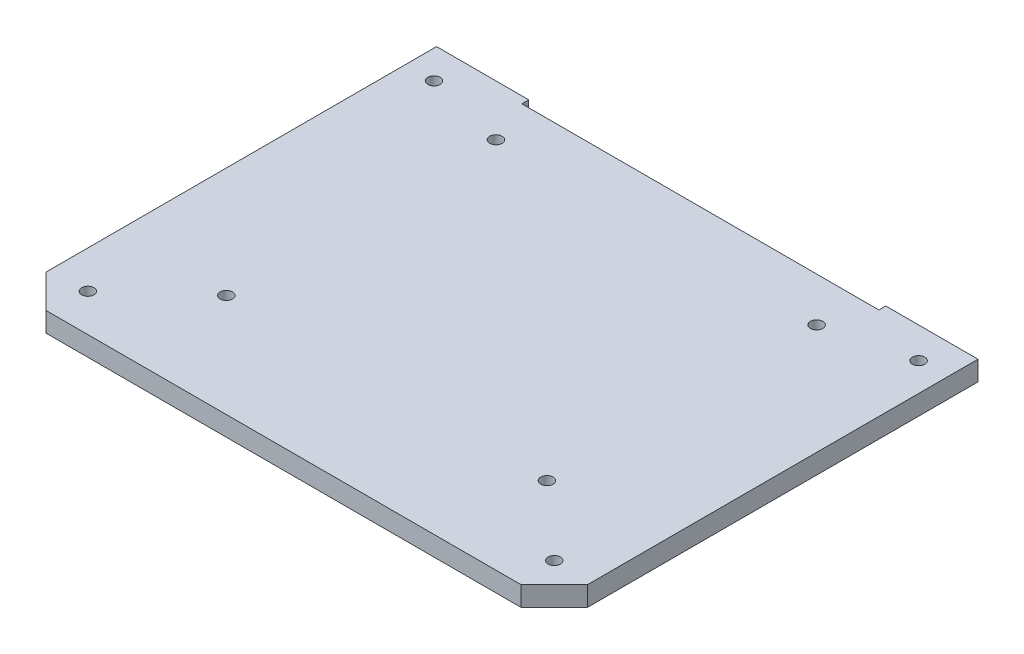
SolidWorks part; units mm, degrees
ref_plane "Front Plane" through (0, 0, 0) normal (0, 0, 1) x (1, 0, 0)
ref_plane "Top Plane" through (0, 0, 0) normal (0, 1, 0) x (1, 0, 0)
ref_plane "Right Plane" through (0, 0, 0) normal (1, 0, 0) x (0, 0, -1)
ref_plane "PZ28" through (0, 28, 0) normal (0, 1, 0) x (1, 0, 0)
sketch "Sketch1" plane through (0, 28, 0) normal (0, 1, 0) x (1, 0, 0)
  line L0 (-65.187, -126.3) -> (65.187, -126.3)
  line L1 (65.187, -126.3) -> (74.3, -117.187)
  line L2 (74.3, -117.187) -> (74.3, -11.9)
  line L3 (74.3, -11.9) -> (-74.3, -11.9)
  line L4 (-74.3, -11.9) -> (-74.3, -117.187)
  line L5 (-74.3, -117.187) -> (-65.187, -126.3)
extrude "Lid Plate" add sketch "Sketch1" along normal blind 2.4
ref_plane "PZ25" through (0, 25, 0) normal (0, 1, 0) x (1, 0, 0)
sketch "Sketch2" plane through (0, 25, 0) normal (0, 1, 0) x (1, 0, 0)
  line L0 (74.3, -11.9) -> (74.3, -117.187)
  line L1 (74.3, -117.187) -> (65.187, -126.3)
  line L2 (65.187, -126.3) -> (-65.187, -126.3)
  line L3 (-65.187, -126.3) -> (-74.3, -117.187)
  line L4 (-74.3, -117.187) -> (-74.3, -11.9)
  line L5 (-74.3, -11.9) -> (-72.7, -11.9)
  line L6 (-72.7, -11.9) -> (-72.7, -116.5243)
  line L7 (-72.7, -116.5243) -> (-64.5243, -124.7)
  line L8 (-64.5243, -124.7) -> (64.5243, -124.7)
  line L9 (64.5243, -124.7) -> (72.7, -116.5243)
  line L10 (72.7, -116.5243) -> (72.7, -11.9)
  line L11 (72.7, -11.9) -> (74.3, -11.9)
extrude "Drip Skirt" add sketch "Sketch2" along normal blind 3.01
sketch "Sketch3" plane through (0, 25, 0) normal (0, 1, 0) x (1, 0, 0)
  line L0 (-74.3, -11.9) -> (-49, -11.9)
  line L1 (-49, -11.9) -> (-49, -10)
  line L2 (-49, -10) -> (-74.3, -10)
  line L3 (-74.3, -10) -> (-74.3, -11.9)
extrude "Front Skirt L" add sketch "Sketch3" along normal blind 5.4
sketch "Sketch4" plane through (0, 25, 0) normal (0, 1, 0) x (1, 0, 0)
  line L0 (49, -11.9) -> (74.3, -11.9)
  line L1 (74.3, -11.9) -> (74.3, -10)
  line L2 (74.3, -10) -> (49, -10)
  line L3 (49, -10) -> (49, -11.9)
extrude "Front Skirt R" add sketch "Sketch4" along normal blind 5.4
ref_plane "PZ27" through (0, 27, 0) normal (0, 1, 0) x (1, 0, 0)
sketch "Sketch5" plane through (0, 27, 0) normal (0, 1, 0) x (1, 0, 0)
  circle A0 centre (-66.5, -18.5) radius 1.7
  circle A1 centre (66.5, -18.5) radius 1.7
  circle A2 centre (-64, -116) radius 1.7
  circle A3 centre (64, -116) radius 1.7
  circle A4 centre (-44, -24) radius 1.7
  circle A5 centre (-44, -98) radius 1.7
  circle A6 centre (44, -24) radius 1.7
  circle A7 centre (44, -98) radius 1.7
extrude "Screw Holes" cut sketch "Sketch5" along normal blind 4.4
equation "\"BOARD_REAR\" = 86.0"
equation "\"BOARD_FRONT\" = 41.0"
equation "\"BOARD_END\" = 22.0"
equation "\"BOARD_ANGLED\" = 30.0"
equation "\"BOARD_DEPTH\" = 41.8431"
equation "\"PCB_T\" = 1.6"
equation "\"ABOVE_PCB\" = 14.0"
equation "\"BELOW_PCB\" = 6.0"
equation "\"MID_PARTS_H\" = 9.0"
equation "\"BOARD_HOLE_PILOT\" = 1.6"
equation "\"J2_X\" = 19.0"
equation "\"DUPONT_DROP\" = 14.0"
equation "\"BEND_R\" = 5.0"
equation "\"BOARD_GAP\" = 3.0"
equation "\"TOF_FOV\" = 25.0"
equation "\"TOF_MARGIN_DEG\" = 5.0"
equation "\"TOF_WIN_MARGIN\" = 1.0"
equation "\"TOF_Z\" = 9.0"
equation "\"TOF_SIDE_BEARING\" = 90.0"
equation "\"TOF_CONE_LEN\" = 70.0"
equation "\"CAM_W\" = 29.2"
equation "\"CAM_H\" = 28.2"
equation "\"CAM_D\" = 12.35"
equation "\"CAM_FRONT_Y\" = 43.0"
equation "\"CAM_BOTTOM_Z\" = 17.0"
equation "\"CAM_LENS_UP\" = 11.6"
equation "\"CAM_LENS_OPEN\" = 9.6"
equation "\"CAM_HFOV\" = 53.5"
equation "\"CAM_VFOV\" = 41.41"
equation "\"CAM_FOV_MARGIN\" = 3.0"
equation "\"CAM_FIT\" = 0.3"
equation "\"RIBBON_W\" = 16.0"
equation "\"RIBBON_T\" = 0.3"
equation "\"RIBBON_LEN\" = 150.0"
equation "\"RIBBON_EXIT_Y\" = 35.0"
equation "\"WALL\" = 2.4"
equation "\"HEAD_X\" = 48.4"
equation "\"HEAD_REAR_Y\" = -11.9"
equation "\"CAM_FOAM\" = 2.8"
equation "\"HEAD_FRONT_Y\" = 48.2"
equation "\"HEAD_TOP_Z\" = 50.6"
equation "\"HEAD_BOT_Z\" = -28.4"
equation "\"HEAD_SPLIT_Z\" = -4.0"
equation "\"SKIRT_T\" = 1.2"
equation "\"SKIRT_H\" = 3.0"
equation "\"SKIRT_FIT\" = 0.3"
equation "\"VISOR\" = 7.8"
equation "\"VISOR_Z\" = 40.0"
equation "\"ROOF_SLOPE_Y\" = 40.0"
equation "\"ROOF_CHAMFER\" = 10.0"
equation "\"REAR_CHAMFER\" = 10.0"
equation "\"CORNER_CHAMFER\" = 6.0"
equation "\"LOWER_SIDE_FACET\" = 6.0"
equation "\"LIGHTBAR_DEPTH\" = 1.0"
equation "\"HOOD_Z\" = 14.0"
equation "\"HOOD_L\" = 6.0"
equation "\"SIDE_HOOD_L\" = 4.0"
equation "\"INSERT_M3_D\" = 4.0"
equation "\"INSERT_M3_L\" = 6.0"
equation "\"M3_CLEAR\" = 3.4"
equation "\"M2_PILOT\" = 1.6"
equation "\"M25_PILOT\" = 2.2"
equation "\"BOX_X\" = 72.4"
equation "\"BOX_FRONT_Y\" = -11.9"
equation "\"BOX_REAR_Y\" = -124.4"
equation "\"BOX_BOT_Z\" = -28.4"
equation "\"BOX_TOP_Z\" = 28.0"
equation "\"LID_T\" = 2.4"
equation "\"LID_SKIRT\" = 1.6"
equation "\"LID_TONGUE_H\" = 3.0"
equation "\"LID_FIT\" = 0.3"
equation "\"PI_STANDOFF\" = 10.0"
equation "\"BOX_REAR_CHAMFER\" = 8.0"
equation "\"BOX_REAR_FACET\" = 4.0"
equation "\"VENT_UPSTAND\" = 3.0"
equation "\"TUBE_D\" = 22.2"
equation "\"TUBE_LINER\" = 1.0"
equation "\"MOUNT_Y\" = -70.0"
equation "\"RAIL_W\" = 30.0"
equation "\"RAIL_W2\" = 38.0"
equation "\"RAIL_H\" = 6.0"
equation "\"SLIDE\" = 0.3"
equation "\"STOP_T\" = 6.0"
equation "\"CLAMP_W\" = 40.0"
equation "\"CLAMP_HALF\" = 20.0"
equation "\"CLAMP_DROP\" = 12.0"
equation "\"CAP_T\" = 12.0"
equation "\"CLAMP_BOLT_OFF\" = 16.6"
equation "\"M5_INSERT_D\" = 6.4"
equation "\"M5_CLEAR\" = 5.5"
equation "\"LOCK_D\" = 3.3"
equation "\"POD_TILT_DEG\" = 0.0"
equation "\"PRINT_LIMIT\" = 180.0"
equation "\"PI5_L\" = 85.0"
equation "\"PI5_W\" = 56.0"
equation "\"PI5_T\" = 1.6"
equation "\"PI5_USBC_BX\" = 11.2"
equation "\"PI5_ETH_BY\" = 10.2"
equation "\"PI5_PORT_OVERHANG\" = 3.0"
equation "\"PI5_FPC_H\" = 5.0"
equation "\"PI5_FPC_USE\" = 0.0"
equation "\"PI5_PIN1_BX\" = 8.37"
equation "\"HEADER_BASE_H\" = 2.5"
equation "\"DUPONT_L\" = 14.0"
equation "\"PI5_UNDERSIDE\" = 1.5"
equation "\"COOLER_H\" = 15.0"
equation "\"HAT_W\" = 65.0"
equation "\"HAT_D\" = 56.5"
equation "\"HAT_T\" = 1.6"
equation "\"HAT_SPACER\" = 16.0"
equation "\"HAILO_H\" = 10.0"
equation "\"STACK_PINS_H\" = 6.0"
equation "\"DUPONT_SEAT\" = 0.5"
equation "\"PCIE_FFC_LOOP\" = 6.0"
equation "\"HAILO_AIR_GAP_MIN\" = 8.0"
equation "\"M25_CLEAR\" = 2.7"
equation "\"PI_X0\" = -55.0"
equation "\"PI_Y1\" = -36.5"
equation "\"PI_Y0\" = -92.5"
equation "\"BOX_LEN\" = 112.5"
equation "\"COVER_T\" = 3.0"
equation "\"COVER_TOP_Z\" = 6.5"
equation "\"SIDE_LEDGE_Z\" = -0.5"
equation "\"UPPER_LEDGE_Z\" = 17.0"
equation "\"REAR_LEDGE_Z\" = 8.0"
equation "\"LEDGE_L\" = 4.0"
equation "\"LEDGE_TIP\" = 1.5"
equation "\"RIBBON_W_PI\" = 11.5"
equation "\"RIBBON_RUN_Z\" = 12.0"
equation "\"RIBBON_SPEC_LEN\" = 200.0"
